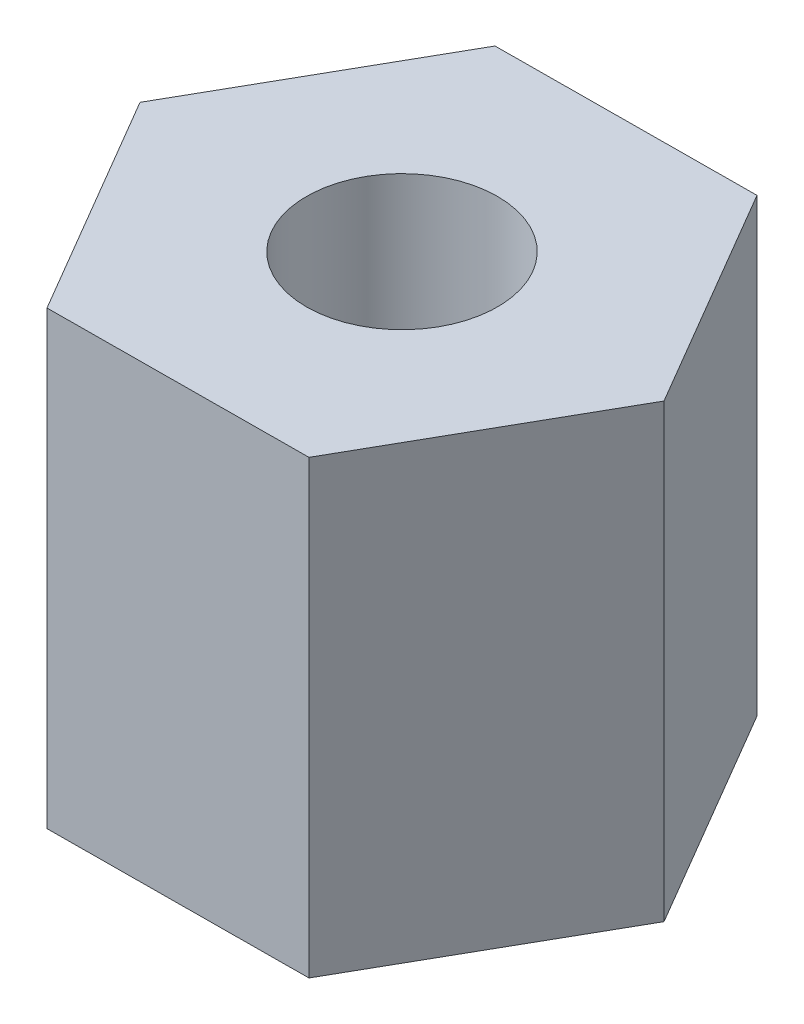
SolidWorks part; units mm, degrees
material "Stainless Steel (ferritic)"
ref_plane "Front Plane" through (0, 0, 0) normal (0, 0, 1) x (1, 0, 0)
ref_plane "Top Plane" through (0, 0, 0) normal (0, 1, 0) x (1, 0, 0)
ref_plane "Right Plane" through (0, 0, 0) normal (1, 0, 0) x (0, 0, -1)
sketch "Sketch2" plane through (0, 0, 0) normal (0, 1, 0) x (1, 0, 0)
  line L1 (2.9186, -4.9814) -> (5.7734, 0.0369)
  line L2 (5.7734, 0.0369) -> (2.8547, 5.0183)
  line L3 (2.8547, 5.0183) -> (-2.9186, 4.9814)
  line L4 (-2.9186, 4.9814) -> (-5.7734, -0.0369)
  line L5 (-5.7734, -0.0369) -> (-2.8547, -5.0183)
  line L6 (-2.8547, -5.0183) -> (2.9186, -4.9814)
  circle A0 centre (0, 0) radius 5 construction
  circle A1 centre (0, 0) radius 2.1209
  dimension "D3" = 4.2418
  dimension "D1" = 10
  dimension "D2" = 5.7734
extrude "Boss-Extrude1" add sketch "Sketch2" along normal blind 10
